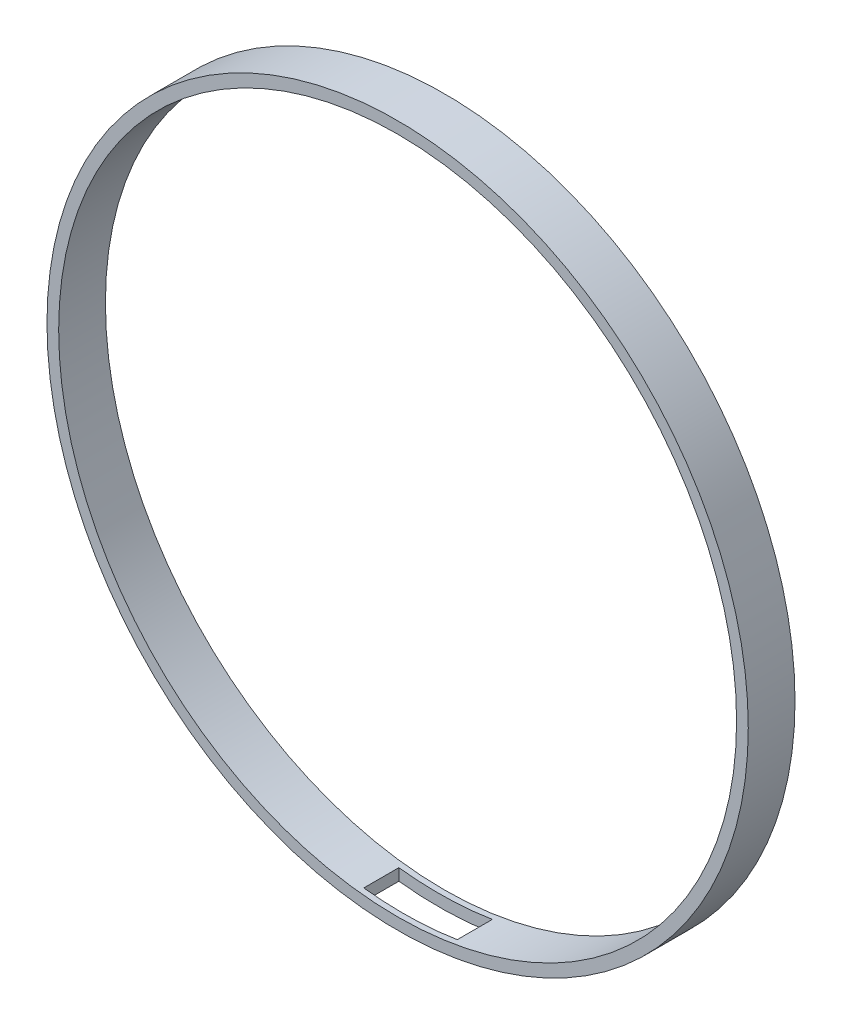
SolidWorks part; units mm, degrees
ref_plane "Front Plane" through (0, 0, 0) normal (0, 0, 1) x (1, 0, 0)
ref_plane "Top Plane" through (0, 0, 0) normal (0, 1, 0) x (1, 0, 0)
ref_plane "Right Plane" through (0, 0, 0) normal (1, 0, 0) x (0, 0, -1)
sketch "Sketch1" plane through (0, 0, 0) normal (0, 0, 1) x (1, 0, 0)
  circle A0 centre (0, 0) radius 190.5
  dimension "D1" = 381
extrude "Boss-Extrude1" add sketch "Sketch1" along normal blind 25.4
sketch "Sketch2" plane through (0, 0, 25.4) normal (0, 0, 1) x (1, 0, 0)
  circle A0 centre (0, 0) radius 184.15
  circle A1 centre (0, 0) radius 190.5 construction
  dimension "D1" = 6.35
extrude "Cut-Extrude1" cut sketch "Sketch2" against normal blind 25.4
sketch "Sketch3" plane through (0, 0, 0) normal (0, 1, 0) x (1, 0, 0)
  line L1 (-21.5647, -3.175) -> (29.2353, -3.175)
  line L2 (-21.5647, -3.175) -> (-21.5647, -22.225)
  line L3 (-21.5647, -22.225) -> (29.2353, -22.225)
  line L4 (29.2353, -3.175) -> (29.2353, -22.225)
  line L6 (190.5, 0) -> (-190.5, 0) construction
  dimension "D1" = 19.05
  dimension "D2" = 50.8
  dimension "D3" = 3.175
extrude "Cut-Extrude2" cut sketch "Sketch3" against normal up to surface (188.2433 mm away)
